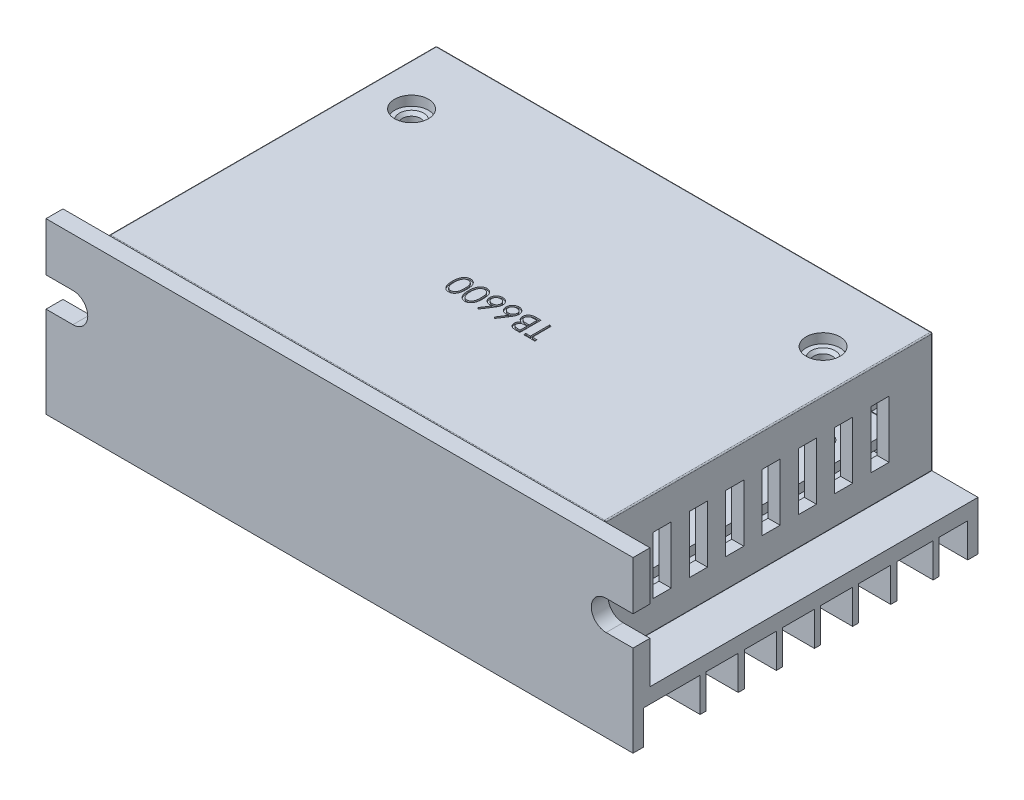
SolidWorks part; units mm, degrees
ref_plane "Front Plane" through (0, 0, 0) normal (0, 0, 1) x (1, 0, 0)
ref_plane "Top Plane" through (0, 0, 0) normal (0, 1, 0) x (1, 0, 0)
ref_plane "Right Plane" through (0, 0, 0) normal (1, 0, 0) x (0, 0, -1)
sketch "Sketch1" plane through (0, 0, 0) normal (1, 0, 0) x (0, 0, -1)
  line L1 (-28.5, 14) -> (28.5, 14)
  line L2 (-28.5, 14) -> (-28.5, -14)
  line L3 (-28.5, -14) -> (28.5, -14)
  line L4 (28.5, 14) -> (28.5, -14)
  line L5 (-28.5, 14) -> (28.5, -14) construction
  line L6 (-28.5, -14) -> (28.5, 14) construction
  point P0 (0, 0)
  dimension "D1" = 28
  dimension "D2" = 57
extrude "Base and Heat Sink" add sketch "Sketch1" along normal mid plane 97
sketch "Sketch2" plane through (0, 0, 0) normal (1, 0, 0) x (0, 0, -1)
  line L0 (28.5, 14) -> (-28.5, 14) construction
  line L1 (-25.7, 14) -> (28.5, 14)
  line L2 (-25.7, 14) -> (-25.7, -5.88)
  line L3 (-25.7, -5.88) -> (28.5, -5.88)
  line L4 (28.5, 14) -> (28.5, -5.88)
  line L5 (28.5, -14) -> (28.5, 14) construction
  line L6 (-28.5, 14) -> (-28.5, -14) construction
  line L7 (-28.5, -14) -> (28.5, -14) construction
  dimension "D1" = 2.8
  dimension "D2" = 8.12
extrude "Cut-Extrude1" cut sketch "Sketch2" against normal through all both and the other way through all
sketch "Sketch3" plane through (0, 0, 0) normal (1, 0, 0) x (0, 0, -1)
  line L0 (-28.5, -14) -> (28.5, -14) construction
  line L1 (-26.8, -14) -> (-17.42, -14)
  line L2 (-26.8, -14) -> (-26.8, -8.38)
  line L3 (-26.8, -8.38) -> (-17.42, -8.38)
  line L4 (-17.42, -14) -> (-17.42, -8.38)
  line L5 (-28.5, 14) -> (-28.5, -14) construction
  line L6 (-25.7, -5.88) -> (28.5, -5.88) construction
  line L7 (-10.12, -14) -> (-10.12, -8.38)
  line L8 (-16.42, -14) -> (-11.12, -14)
  line L9 (-16.42, -14) -> (-16.42, -8.38)
  line L10 (-16.42, -8.38) -> (-11.12, -8.38)
  line L11 (-11.12, -14) -> (-11.12, -8.38)
  line L12 (-10.12, -14) -> (-4.82, -14)
  line L13 (-4.82, -14) -> (-4.82, -8.38)
  line L14 (-3.82, -14) -> (-3.82, -8.38)
  line L15 (-3.82, -14) -> (1.48, -14)
  line L16 (1.48, -14) -> (1.48, -8.38)
  line L17 (2.48, -14) -> (2.48, -8.38)
  line L18 (2.48, -14) -> (7.78, -14)
  line L19 (7.78, -14) -> (7.78, -8.38)
  line L20 (8.78, -14) -> (8.78, -8.38)
  line L21 (8.78, -14) -> (14.08, -14)
  line L22 (14.08, -14) -> (14.08, -8.38)
  line L23 (28.5, -14) -> (28.5, -5.88) construction
  line L24 (15.08, -14) -> (21.08, -14)
  line L25 (15.08, -14) -> (15.08, -8.38)
  line L26 (15.08, -8.38) -> (21.08, -8.38)
  line L27 (21.08, -14) -> (21.08, -8.38)
  line L28 (22.08, -14) -> (26.8, -14)
  line L29 (22.08, -14) -> (22.08, -8.38)
  line L30 (22.08, -8.38) -> (26.8, -8.38)
  line L31 (26.8, -14) -> (26.8, -8.38)
  line L32 (-10.12, -8.38) -> (-4.82, -8.38)
  line L33 (-3.82, -8.38) -> (1.48, -8.38)
  line L34 (2.48, -8.38) -> (7.78, -8.38)
  line L35 (8.78, -8.38) -> (14.08, -8.38)
  dimension "D1" = 1.7
  dimension "D2" = 9.38
  dimension "D3" = 2.5
  dimension "D4" = 1
  dimension "D5" = 5.3
  dimension "D7" = 1
  dimension "D8" = 1
  dimension "D9" = 1
  dimension "D10" = 6
  dimension "D11" = 1
  dimension "D12" = 1.7
  dimension "D6" = 5
extrude "Cut-Extrude2" cut sketch "Sketch3" against normal through all both and the other way through all
sketch "Sketch4" plane through (0, -5.88, 0) normal (0, 1, 0) x (1, 0, 0)
  line L2 (-34, -20.8) -> (34, -20.8) construction
  line L3 (-34, -20.8) -> (-34, 17.4) construction
  line L4 (-34, 17.4) -> (34, 17.4) construction
  line L5 (34, -20.8) -> (34, 17.4) construction
  line L6 (-34, -20.8) -> (34, 17.4) construction
  line L7 (-34, 17.4) -> (34, -20.8) construction
  line L8 (-48.5, 28.5) -> (48.5, 28.5) construction
  circle A0 centre (-34, 17.4) radius 1.5
  circle A1 centre (34, 17.4) radius 1.5
  circle A2 centre (34, -20.8) radius 1.5
  circle A3 centre (-34, -20.8) radius 1.5
  point P0 (0, -1.7)
  dimension "D4" = 3
  dimension "D1" = 68
  dimension "D2" = 11.1
  dimension "D3" = 38.2
extrude "Cut-Extrude3" cut sketch "Sketch4" against normal blind 3
sketch "Sketch5" plane through (0, 0, 28.5) normal (0, 0, 1) x (1, 0, 0)
  line L0 (-48.5, 3.5) -> (52.8108, 3.5) construction
  line L1 (-48.5, 14) -> (-48.5, -14) construction
  line L2 (48.5, 14) -> (-48.5, 14) construction
  line L3 (48.5, 14) -> (48.5, -14) construction
  line L4 (41.6, 6.1377) -> (41.6, 0) construction
  line L5 (44.05, 1.05) -> (48.5, 1.05)
  line L6 (44.05, 5.95) -> (48.5, 5.95)
  line L7 (-41.6, 1.05) -> (-41.6, 6.49) construction
  line L8 (-44.05, 5.95) -> (-48.5, 5.95)
  line L9 (-44.05, 1.05) -> (-48.5, 1.05)
  line L10 (-48.5, 1.05) -> (-48.5, 5.95)
  line L11 (48.5, 1.05) -> (48.5, 5.95)
  arc A0 (44.05, 5.95) -> (44.05, 1.05) centre (44.05, 3.5) ccw
  arc A1 (-44.05, 1.05) -> (-44.05, 5.95) centre (-44.05, 3.5) ccw
  dimension "D2" = 4.9
  dimension "D4" = 6.9
  dimension "D1" = 10.5
  dimension "D3" = 4.45
extrude "Cut-Extrude4" cut sketch "Sketch5" against normal blind 3
sketch "Sketch6" plane through (0, 0, 0) normal (1, 0, 0) x (0, 0, -1)
  line L0 (-25.7, 14) -> (-25.7, 5.95) construction
  line L1 (-25.7, 14) -> (28.5, 14)
  line L2 (-25.7, 14) -> (-25.7, -5.88)
  line L3 (-25.7, -5.88) -> (28.5, -5.88)
  line L4 (28.5, 14) -> (28.5, -5.88)
  line L5 (-25.7, 14) -> (-28.5, 14) construction
extrude "Plastic Casing" add sketch "Sketch6" along normal mid plane 82 separate body
shell "Shell1" thickness 2
fillet "Fillet1" radius 0.2 11 edges at (-41, -5.88, -1.4) (-41, 4.06, 25.7) (0, 14, 25.7) (-41, 14, -1.4) (0, -5.88, -28.5) (0, 14, -28.5) (-41, 4.06, -28.5) (41, 14, -1.4) (41, 4.06, -28.5) (41, -5.88, -1.4) (41, 4.06, 25.7)
sketch "Sketch9" plane through (0, 14, 0) normal (0, 1, 0) x (1, 0, 0)
  circle A0 centre (-34, 17.4) radius 1.5 construction
  circle A1 centre (34, 17.4) radius 1.5 construction
  circle A2 centre (-34, 17.4) radius 1.5
  circle A3 centre (34, 17.4) radius 1.5
sketch "Sketch10" plane through (0, 12, 0) normal (0, -1, 0) x (1, 0, 0)
  circle A0 centre (34, -17.4) radius 3.975
  circle A1 centre (-34, -17.4) radius 3.975
  dimension "D1" = 7.95
extrude "Boss-Extrude3" add sketch "Sketch10" along normal blind 1.2
sketch "Sketch11" plane through (0, 10.8, 0) normal (0, -1, 0) x (1, 0, 0)
  circle A0 centre (-34, -17.4) radius 1.5 construction
  circle A1 centre (34, -17.4) radius 1.5 construction
  circle A2 centre (-34, -17.4) radius 1.5
  circle A3 centre (34, -17.4) radius 1.5
extrude "Cut-Extrude5" cut sketch "Sketch11" against normal blind 11.2
sketch "Sketch12" plane through (0, 14, 0) normal (0, 1, 0) x (1, 0, 0)
  circle A0 centre (-34, 17.4) radius 2.8
  circle A1 centre (34, 17.4) radius 2.8
  dimension "D1" = 5.6
extrude "Cut-Extrude6" cut sketch "Sketch12" against normal blind 1.6
chamfer "Chamfer1" distance 0.5 angle 45 2 edges at (34, 12.4, -15.9) (-34, 12.4, -15.9)
sketch "Sketch13" plane through (0, 0, -28.5) normal (0, 0, -1) x (-1, 0, 0)
  line L0 (41, 13.8) -> (41, -5.68) construction
  line L1 (-33.9, -0.38) -> (32.5, -0.38)
  line L2 (-33.9, -0.38) -> (-33.9, 10.25)
  line L3 (-33.9, 10.25) -> (32.5, 10.25)
  line L4 (32.5, -0.38) -> (32.5, 10.25)
  line L5 (-41, -5.68) -> (-41, 13.8) construction
  line L6 (-40.8, 14) -> (40.8, 14) construction
  line L7 (40.8, -5.88) -> (-40.8, -5.88) construction
  dimension "D1" = 8.5
  dimension "D2" = 7.1
  dimension "D3" = 3.75
  dimension "D4" = 5.5
extrude "Cut-Extrude7" cut sketch "Sketch13" against normal up to surface (2 mm away) up to face at (0, 3.06, -26.5)
sketch "Sketch14" plane through (0, 0, 0) normal (1, 0, 0) x (0, 0, -1)
  line L0 (28.5, -5.68) -> (28.5, 13.8) construction
  line L1 (21.3, 8.45) -> (18.3, 8.45)
  line L2 (21.3, 8.45) -> (21.3, -1.0244)
  line L3 (21.3, -1.0244) -> (18.3, -1.0244)
  line L4 (18.3, 8.45) -> (18.3, -1.0244)
  line L5 (28.3, 14) -> (-25.5, 14) construction
  line L7 (15.3, 8.45) -> (12.3, 8.45)
  line L8 (15.3, 8.45) -> (15.3, -1.0244)
  line L9 (15.3, -1.0244) -> (12.3, -1.0244)
  line L10 (12.3, 8.45) -> (12.3, -1.0244)
  line L11 (9.3, 8.45) -> (6.3, 8.45)
  line L12 (9.3, 8.45) -> (9.3, -1.0244)
  line L13 (9.3, -1.0244) -> (6.3, -1.0244)
  line L14 (6.3, 8.45) -> (6.3, -1.0244)
  line L15 (3.3, 8.45) -> (0.3, 8.45)
  line L16 (3.3, 8.45) -> (3.3, -1.0244)
  line L17 (3.3, -1.0244) -> (0.3, -1.0244)
  line L18 (0.3, 8.45) -> (0.3, -1.0244)
  line L19 (-2.7, 8.45) -> (-5.7, 8.45)
  line L20 (-2.7, 8.45) -> (-2.7, -1.0244)
  line L21 (-2.7, -1.0244) -> (-5.7, -1.0244)
  line L22 (-5.7, 8.45) -> (-5.7, -1.0244)
  line L23 (-8.7, 8.45) -> (-11.7, 8.45)
  line L24 (-8.7, 8.45) -> (-8.7, -1.0244)
  line L25 (-8.7, -1.0244) -> (-11.7, -1.0244)
  line L26 (-11.7, 8.45) -> (-11.7, -1.0244)
  line L27 (-14.7, 8.45) -> (-17.7, 8.45)
  line L28 (-14.7, 8.45) -> (-14.7, -1.0244)
  line L29 (-14.7, -1.0244) -> (-17.7, -1.0244)
  line L30 (-17.7, 8.45) -> (-17.7, -1.0244)
  dimension "D1" = 7.2
  dimension "D2" = 3
  dimension "D3" = 5.55
  dimension "D4" = 7
extrude "Cut-Extrude9" cut sketch "Sketch14" along normal up to surface (41 mm away) up to face at (41, 4.06, -1.4)
sketch "Sketch15" plane through (-41, 0, 0) normal (-1, 0, 0) x (0, 0, 1)
  line L0 (14.7, 8.45) -> (14.7, -1.0244) construction
  line L1 (17.7, 8.45) -> (14.7, 8.45) construction
  line L2 (17.7, -1.0244) -> (17.7, 8.45) construction
  line L3 (14.7, -1.0244) -> (17.7, -1.0244) construction
  line L4 (8.7, -1.0244) -> (11.7, -1.0244) construction
  line L5 (8.7, 8.45) -> (8.7, -1.0244) construction
  line L6 (11.7, 8.45) -> (8.7, 8.45) construction
  line L7 (11.7, -1.0244) -> (11.7, 8.45) construction
  line L8 (-21.3, -1.0244) -> (-18.3, -1.0244) construction
  line L9 (-21.3, 8.45) -> (-21.3, -1.0244) construction
  line L10 (-18.3, 8.45) -> (-21.3, 8.45) construction
  line L11 (-18.3, -1.0244) -> (-18.3, 8.45) construction
  line L12 (14.7, 8.45) -> (14.7, -1.0244)
  line L13 (17.7, 8.45) -> (14.7, 8.45)
  line L14 (17.7, -1.0244) -> (17.7, 8.45)
  line L15 (14.7, -1.0244) -> (17.7, -1.0244)
  line L16 (8.7, -1.0244) -> (11.7, -1.0244)
  line L17 (8.7, 8.45) -> (8.7, -1.0244)
  line L18 (11.7, 8.45) -> (8.7, 8.45)
  line L19 (11.7, -1.0244) -> (11.7, 8.45)
  line L20 (-21.3, -1.0244) -> (-18.3, -1.0244)
  line L21 (-21.3, 8.45) -> (-21.3, -1.0244)
  line L22 (-18.3, 8.45) -> (-21.3, 8.45)
  line L23 (-18.3, -1.0244) -> (-18.3, 8.45)
extrude "Cut-Extrude10" cut sketch "Sketch15" against normal up to surface (2 mm away) up to face at (-39, 3.06, -0.4)
sketch "Sketch16" plane through (-41, 0, 0) normal (-1, 0, 0) x (0, 0, 1)
  line L0 (25.7, -5.88) -> (-28.3, -5.88) construction
  line L1 (-15.1674, 10.82) -> (3.6826, 10.82)
  line L2 (-15.1674, 10.82) -> (-15.1674, 0.62)
  line L3 (-15.1674, 0.62) -> (3.6826, 0.62)
  line L4 (3.6826, 10.82) -> (3.6826, 0.62)
  dimension "D1" = 18.85
  dimension "D2" = 10.2
  dimension "D3" = 6.5
extrude "Cut-Extrude11" cut sketch "Sketch16" against normal up to surface (2 mm away) up to face at (-39, 3.7128, 10.2)
ref_plane "Plane1" through (0, -0.88, 0) normal (0, 1, 0) x (1, 0, 0)
sketch "Sketch17" plane through (0, -0.88, 0) normal (0, 1, 0) x (1, 0, 0)
  line L0 (-48.5, -25.7) -> (48.5, -25.7) construction
  line L1 (38.275, -24.7) -> (-38.275, -24.7)
  line L2 (38.275, -24.7) -> (38.275, 25.4)
  line L3 (38.275, 25.4) -> (-38.275, 25.4)
  line L4 (-38.275, -24.7) -> (-38.275, 25.4)
  circle A0 centre (-34, -20.8) radius 1.5 construction
  circle A1 centre (-34, 17.4) radius 1.5 construction
  circle A2 centre (34, 17.4) radius 1.5 construction
  circle A3 centre (34, -20.8) radius 1.5 construction
  circle A4 centre (-34, -20.8) radius 1.5
  circle A5 centre (-34, 17.4) radius 1.5
  circle A6 centre (34, 17.4) radius 1.5
  circle A7 centre (34, -20.8) radius 1.5
  point P18 (0, -24.7)
  dimension "D1" = 50.1
  dimension "D2" = 1
  dimension "D3" = 76.55
extrude "Boss-Extrude4" add sketch "Sketch17" along normal blind 1.5 separate body
ref_plane "Plane2" through (0, 0, -33.5) normal (0, 0, -1) x (-1, 0, 0)
sketch "Sketch18" plane through (0, 0, -33.5) normal (0, 0, -1) x (-1, 0, 0)
  line L0 (-38.275, 0.62) -> (38.275, 0.62) construction
  line L1 (-33.9, 0.62) -> (27.4, 0.62)
  line L2 (-33.9, 0.62) -> (-33.9, 8.62)
  line L3 (-33.9, 8.62) -> (27.4, 8.62)
  line L4 (27.4, 0.62) -> (27.4, 8.62)
  line L5 (-33.9, 10.25) -> (-33.9, -0.38) construction
  dimension "D1" = 8
  dimension "D2" = 61.3
extrude "Connector" add sketch "Sketch18" against normal blind 12 separate body
sketch "Sketch19" plane through (0, 0, -33.5) normal (0, 0, -1) x (-1, 0, 0)
  line L0 (-3.3029, 9.6458) -> (-3.3029, -7.8401) construction
  line L1 (-33.9, 7.1295) -> (-33.9, 1.6983) construction
  line L2 (-33.9, 8.62) -> (-33.9, 0.62) construction
  line L3 (-28.7917, 7.1867) -> (-28.7917, 1.7555) construction
  line L4 (-23.6833, 7.2439) -> (-23.6833, 1.8127) construction
  line L5 (-18.575, 7.3012) -> (-18.575, 1.8699) construction
  line L6 (-13.4667, 7.3584) -> (-13.4667, 1.9272) construction
  line L7 (-8.3583, 7.4156) -> (-8.3583, 1.9844) construction
  line L8 (-3.25, 7.4728) -> (-3.25, 2.0416) construction
  line L9 (1.8583, 7.53) -> (1.8583, 2.0988) construction
  line L10 (6.9667, 7.5873) -> (6.9667, 2.1561) construction
  line L11 (12.075, 7.6445) -> (12.075, 2.2133) construction
  line L12 (17.1833, 7.7017) -> (17.1833, 2.2705) construction
  line L13 (22.2917, 7.7589) -> (22.2917, 2.3277) construction
  line L14 (27.4, 7.8162) -> (27.4, 2.385) construction
  line L15 (-33.9, 7.1295) -> (-28.7917, 7.1867) construction
  dimension "D2" = 5.1087
  dimension "D1" = 13
sketch "Sketch20" plane through (0, 0, -33.5) normal (0, 0, -1) x (-1, 0, 0)
  line L0 (-33.9, 8.62) -> (-33.9, 0.62) construction
  line L1 (-33.9, 7.02) -> (27.4, 7.02)
  line L2 (-33.9, 7.02) -> (-33.9, 1.62)
  line L3 (-33.9, 1.62) -> (-33.3515, 1.62)
  line L4 (27.4, 7.02) -> (27.4, 1.62)
  line L5 (27.4, 0.62) -> (27.4, 8.62) construction
  line L6 (27.4, 8.62) -> (-33.9, 8.62) construction
  line L7 (-31.3458, 16.2754) -> (-31.3458, 1.62) construction
  line L8 (-28.7917, 7.1867) -> (-28.7917, 1.7555) construction
  line L9 (-29.3401, 1.62) -> (-28.2394, 1.62)
  line L10 (24.8458, 7.7121) -> (24.8458, 1.62) construction
  line L11 (22.2917, 7.7589) -> (22.2917, 2.3277) construction
  line L12 (-33.3515, 1.62) -> (-28.2402, 1.6208) construction
  line L13 (-24.2297, 1.62) -> (-23.1272, 1.62)
  line L14 (-19.1193, 1.62) -> (-18.0151, 1.62)
  line L15 (-14.0089, 1.62) -> (-12.9029, 1.62)
  line L16 (-8.8985, 1.62) -> (-7.7907, 1.62)
  line L17 (-3.7881, 1.62) -> (-2.6786, 1.62)
  line L18 (1.3223, 1.62) -> (2.4336, 1.62)
  line L19 (6.4327, 1.62) -> (7.5458, 1.62)
  line L20 (11.5432, 1.62) -> (12.6579, 1.62)
  line L21 (16.6536, 1.62) -> (17.7701, 1.62)
  line L22 (21.764, 1.62) -> (22.8823, 1.62)
  line L23 (26.8744, 1.62) -> (27.4, 1.62)
  arc A0 (-33.3515, 1.62) -> (-29.3401, 1.62) centre (-31.3458, 3.7715) ccw
  arc A1 (-28.2394, 1.62) -> (-24.2297, 1.62) centre (-26.2345, 3.7723) ccw
  arc A2 (-23.1272, 1.62) -> (-19.1193, 1.62) centre (-21.1233, 3.7731) ccw
  arc A3 (-18.0151, 1.62) -> (-14.0089, 1.62) centre (-16.012, 3.7739) ccw
  arc A4 (-12.9029, 1.62) -> (-8.8985, 1.62) centre (-10.9007, 3.7748) ccw
  arc A5 (-7.7907, 1.62) -> (-3.7881, 1.62) centre (-5.7894, 3.7756) ccw
  arc A6 (-2.6786, 1.62) -> (1.3223, 1.62) centre (-0.6781, 3.7764) ccw
  arc A7 (2.4336, 1.62) -> (6.4327, 1.62) centre (4.4332, 3.7772) ccw
  arc A8 (7.5458, 1.62) -> (11.5432, 1.62) centre (9.5445, 3.778) ccw
  arc A9 (12.6579, 1.62) -> (16.6536, 1.62) centre (14.6557, 3.7788) ccw
  arc A10 (17.7701, 1.62) -> (21.764, 1.62) centre (19.767, 3.7796) ccw
  arc A11 (22.8823, 1.62) -> (26.8744, 1.62) centre (24.8783, 3.7804) ccw
  dimension "D5" = 2.9414
  dimension "D1" = 5.4
  dimension "D2" = 1.6
  dimension "D4" = 5.1113
  dimension "D3" = 12
extrude "Cut-Extrude12" cut sketch "Sketch20" against normal blind 10.5
sketch "Sketch21" plane through (0, 0, -23) normal (0, 0, -1) x (-1, 0, 0)
  line L0 (-31.3458, 6.0298) -> (-31.3458, 2.1596) construction
  line L1 (-33.9, 7.1295) -> (-33.9, 1.6983) construction
  line L2 (-28.7917, 7.1867) -> (-28.7917, 1.7555) construction
  line L3 (-31.3458, 4.0947) -> (24.8458, 4.0947) construction
  line L4 (24.8458, 6.0298) -> (24.8458, 2.1596) construction
  line L5 (22.2917, 7.7589) -> (22.2917, 2.3277) construction
  line L6 (27.4, 7.8162) -> (27.4, 2.385) construction
  line L7 (-26.4875, 4.3447) -> (-25.9875, 4.3447)
  line L8 (-31.5958, 4.3447) -> (-31.0958, 4.3447)
  line L9 (-31.5958, 4.3447) -> (-31.5958, 3.8447)
  line L10 (-31.5958, 3.8447) -> (-31.0958, 3.8447)
  line L11 (-31.0958, 4.3447) -> (-31.0958, 3.8447)
  line L12 (-31.5958, 4.3447) -> (-31.0958, 3.8447) construction
  line L13 (-31.5958, 3.8447) -> (-31.0958, 4.3447) construction
  line L14 (-26.4875, 4.3447) -> (-26.4875, 3.8447)
  line L15 (-26.4875, 3.8447) -> (-25.9875, 3.8447)
  line L16 (-25.9875, 4.3447) -> (-25.9875, 3.8447)
  line L17 (-26.4875, 4.3447) -> (-25.9875, 3.8447) construction
  line L18 (-26.4875, 3.8447) -> (-25.9875, 4.3447) construction
  line L19 (-21.3792, 4.3447) -> (-20.8792, 4.3447)
  line L20 (-21.3792, 4.3447) -> (-21.3792, 3.8447)
  line L21 (-21.3792, 3.8447) -> (-20.8792, 3.8447)
  line L22 (-20.8792, 4.3447) -> (-20.8792, 3.8447)
  line L23 (-21.3792, 4.3447) -> (-20.8792, 3.8447) construction
  line L24 (-21.3792, 3.8447) -> (-20.8792, 4.3447) construction
  line L25 (-16.2708, 4.3447) -> (-15.7708, 4.3447)
  line L26 (-16.2708, 4.3447) -> (-16.2708, 3.8447)
  line L27 (-16.2708, 3.8447) -> (-15.7708, 3.8447)
  line L28 (-15.7708, 4.3447) -> (-15.7708, 3.8447)
  line L29 (-16.2708, 4.3447) -> (-15.7708, 3.8447) construction
  line L30 (-16.2708, 3.8447) -> (-15.7708, 4.3447) construction
  line L31 (-11.1625, 4.3447) -> (-10.6625, 4.3447)
  line L32 (-11.1625, 4.3447) -> (-11.1625, 3.8447)
  line L33 (-11.1625, 3.8447) -> (-10.6625, 3.8447)
  line L34 (-10.6625, 4.3447) -> (-10.6625, 3.8447)
  line L35 (-11.1625, 4.3447) -> (-10.6625, 3.8447) construction
  line L36 (-11.1625, 3.8447) -> (-10.6625, 4.3447) construction
  line L37 (-6.0542, 4.3447) -> (-5.5542, 4.3447)
  line L38 (-6.0542, 4.3447) -> (-6.0542, 3.8447)
  line L39 (-6.0542, 3.8447) -> (-5.5542, 3.8447)
  line L40 (-5.5542, 4.3447) -> (-5.5542, 3.8447)
  line L41 (-6.0542, 4.3447) -> (-5.5542, 3.8447) construction
  line L42 (-6.0542, 3.8447) -> (-5.5542, 4.3447) construction
  line L43 (-0.9458, 4.3447) -> (-0.4458, 4.3447)
  line L44 (-0.9458, 4.3447) -> (-0.9458, 3.8447)
  line L45 (-0.9458, 3.8447) -> (-0.4458, 3.8447)
  line L46 (-0.4458, 4.3447) -> (-0.4458, 3.8447)
  line L47 (-0.9458, 4.3447) -> (-0.4458, 3.8447) construction
  line L48 (-0.9458, 3.8447) -> (-0.4458, 4.3447) construction
  line L49 (4.1625, 4.3447) -> (4.6625, 4.3447)
  line L50 (4.1625, 4.3447) -> (4.1625, 3.8447)
  line L51 (4.1625, 3.8447) -> (4.6625, 3.8447)
  line L52 (4.6625, 4.3447) -> (4.6625, 3.8447)
  line L53 (4.1625, 4.3447) -> (4.6625, 3.8447) construction
  line L54 (4.1625, 3.8447) -> (4.6625, 4.3447) construction
  line L55 (9.2708, 4.3447) -> (9.7708, 4.3447)
  line L56 (9.2708, 4.3447) -> (9.2708, 3.8447)
  line L57 (9.2708, 3.8447) -> (9.7708, 3.8447)
  line L58 (9.7708, 4.3447) -> (9.7708, 3.8447)
  line L59 (9.2708, 4.3447) -> (9.7708, 3.8447) construction
  line L60 (9.2708, 3.8447) -> (9.7708, 4.3447) construction
  line L61 (14.3792, 4.3447) -> (14.8792, 4.3447)
  line L62 (14.3792, 4.3447) -> (14.3792, 3.8447)
  line L63 (14.3792, 3.8447) -> (14.8792, 3.8447)
  line L64 (14.8792, 4.3447) -> (14.8792, 3.8447)
  line L65 (14.3792, 4.3447) -> (14.8792, 3.8447) construction
  line L66 (14.3792, 3.8447) -> (14.8792, 4.3447) construction
  line L67 (19.4875, 4.3447) -> (19.9875, 4.3447)
  line L68 (19.4875, 4.3447) -> (19.4875, 3.8447)
  line L69 (19.4875, 3.8447) -> (19.9875, 3.8447)
  line L70 (19.9875, 4.3447) -> (19.9875, 3.8447)
  line L71 (19.4875, 4.3447) -> (19.9875, 3.8447) construction
  line L72 (19.4875, 3.8447) -> (19.9875, 4.3447) construction
  line L73 (24.5958, 4.3447) -> (25.0958, 4.3447)
  line L74 (24.5958, 4.3447) -> (24.5958, 3.8447)
  line L75 (24.5958, 3.8447) -> (25.0958, 3.8447)
  line L76 (25.0958, 4.3447) -> (25.0958, 3.8447)
  line L77 (24.5958, 4.3447) -> (25.0958, 3.8447) construction
  line L78 (24.5958, 3.8447) -> (25.0958, 4.3447) construction
  line L79 (-31.5958, 4.3447) -> (-26.4875, 4.3447) construction
  dimension "D1" = 0.5
  dimension "D2" = 0.5
  dimension "D4" = 5.1083
  dimension "D3" = 12
extrude "Boss-Extrude6" add sketch "Sketch21" along normal blind 10.5
chamfer "Chamfer2" distance 0.6 angle 15 48 edges at (-24.8458, 3.8447, -33.5) (-24.5958, 4.0947, -33.5) (-24.8458, 4.3447, -33.5) (-25.0958, 4.0947, -33.5) (-19.7375, 3.8447, -33.5) (-19.4875, 4.0947, -33.5) (-19.7375, 4.3447, -33.5) (-19.9875, 4.0947, -33.5) (-14.6292, 3.8447, -33.5) (-14.3792, 4.0947, -33.5) (-14.6292, 4.3447, -33.5) (-14.8792, 4.0947, -33.5) (-9.5208, 3.8447, -33.5) (-9.2708, 4.0947, -33.5) (-9.5208, 4.3447, -33.5) (-9.7708, 4.0947, -33.5) (-4.4125, 3.8447, -33.5) (-4.1625, 4.0947, -33.5) (-4.4125, 4.3447, -33.5) (-4.6625, 4.0947, -33.5) (0.6958, 3.8447, -33.5) (0.9458, 4.0947, -33.5) (0.6958, 4.3447, -33.5) (0.4458, 4.0947, -33.5) (5.8042, 3.8447, -33.5) (6.0542, 4.0947, -33.5) (5.8042, 4.3447, -33.5) (5.5542, 4.0947, -33.5) (10.9125, 3.8447, -33.5) (11.1625, 4.0947, -33.5) (10.9125, 4.3447, -33.5) (10.6625, 4.0947, -33.5) (16.0208, 3.8447, -33.5) (16.2708, 4.0947, -33.5) (16.0208, 4.3447, -33.5) (15.7708, 4.0947, -33.5) (21.1292, 3.8447, -33.5) (21.3792, 4.0947, -33.5) (21.1292, 4.3447, -33.5) (20.8792, 4.0947, -33.5) (26.2375, 3.8447, -33.5) (26.4875, 4.0947, -33.5) (26.2375, 4.3447, -33.5) (25.9875, 4.0947, -33.5) (31.3458, 3.8447, -33.5) (31.5958, 4.0947, -33.5) (31.3458, 4.3447, -33.5) (31.0958, 4.0947, -33.5)
ref_plane "Lights" through (0, 0, -29.5) normal (0, 0, -1) x (-1, 0, 0)
sketch "Sketch22" plane through (0, 0, -29.5) normal (0, 0, -1) x (-1, 0, 0)
  line L0 (27.4, 0.62) -> (27.4, 8.62) construction
  line L1 (27.4, 0.62) -> (32.5, 0.62)
  line L2 (27.4, 0.62) -> (27.4, 10.25)
  line L3 (27.4, 10.25) -> (32.5, 10.25)
  line L4 (32.5, 0.62) -> (32.5, 10.25)
  line L5 (-38.275, 0.62) -> (38.275, 0.62) construction
extrude "Boss-Extrude7" add sketch "Sketch22" against normal blind 9 separate body
sketch "Sketch23" plane through (0, 0, -29.5) normal (0, 0, -1) x (-1, 0, 0)
  line L0 (29.95, 10.25) -> (29.95, 0.62) construction
  line L1 (32.5, 10.25) -> (27.4, 10.25) construction
  line L2 (27.4, 0.62) -> (32.5, 0.62) construction
  circle A0 centre (29.95, 7.04) radius 1
  dimension "D2" = 2
  dimension "D4" = 3.21
extrude "Boss-Extrude8" add sketch "Sketch23" along normal blind 4 separate body
sketch "Sketch24" plane through (0, 0, -33.5) normal (0, 0, -1) x (-1, 0, 0)
  line L0 (29.95, 8.2458) -> (29.95, 5.8056) construction
ref_plane "Plane4" through (-29.95, 0, 0) normal (-1, 0, 0) x (0, 0, 1)
sketch "Sketch26" plane through (-29.95, 0, 0) normal (-1, 0, 0) x (0, 0, 1)
  line L0 (-33.8971, 7.04) -> (-31.2542, 7.04) construction
  line L3 (-33.5, 6.04) -> (-32.3126, 6.04) construction
  line L6 (-33.5, 8.04) -> (-33.5, 6.04) construction
  line L7 (-33.5, 8.04) -> (-32.6838, 8.04) construction
  line L8 (-29.5, 10.714) -> (-29.5, -10.714) construction
  line L9 (-33, 7.04) -> (-33.7369, 7.04)
  line L10 (-33.7369, 7.04) -> (-33.7369, 6.04)
  line L11 (-33.7369, 6.04) -> (-32, 6.04)
  arc A0 (-33, 7.04) -> (-32, 6.04) centre (-32, 7.04) ccw
  dimension "D2" = 2
  dimension "D1" = 1
  dimension "D3" = 2.5
revolve "Cut-Revolve2" cut sketch "Sketch26" angle 360 about L0
sketch "Sketch27" plane through (0, 0, -29.5) normal (0, 0, -1) x (-1, 0, 0)
  line L0 (29.95, 10.25) -> (29.95, 0.6198) construction
  line L1 (32.5, 10.25) -> (27.4, 10.25) construction
  line L2 (29.95, -5.2965) -> (29.95, 5.2965) construction
  line L3 (27.4, 0.62) -> (32.5, 0.62) construction
  circle A0 centre (29.95, 3.83) radius 1
  dimension "D1" = 2
  dimension "D2" = 3.21
extrude "Boss-Extrude9" add sketch "Sketch27" along normal blind 4 separate body
sketch "Sketch28" plane through (-29.95, 0, 0) normal (-1, 0, 0) x (0, 0, 1)
  line L0 (-33.7212, 3.83) -> (-29.3271, 3.83) construction
  line L1 (-29.5, 4.83) -> (-33.5, 4.83) construction
  line L2 (-33.5, 2.83) -> (-29.5, 2.83) construction
  line L3 (-32, 8.04) -> (-32, 6.04) construction
  line L4 (-32, 7.04) -> (-32, 2.3515) construction
  line L5 (-32, 2.83) -> (-33.7212, 2.83)
  line L6 (-33.7212, 2.83) -> (-33.7212, 3.83)
  line L7 (-33.7212, 3.83) -> (-33, 3.83)
  arc A0 (-33, 3.83) -> (-32, 2.83) centre (-32, 3.83) ccw
  dimension "D1" = 2
revolve "Cut-Revolve3" cut sketch "Sketch28" angle 360 about L0
sketch "Sketch29" plane through (0, 0.62, 0) normal (0, 1, 0) x (1, 0, 0)
  line L0 (-40.8, 5.7424) -> (-12.823, 5.7424) construction
  line L1 (-40.8, 28.3) -> (-40.8, -25.5) construction
  line L2 (-40, 15.1674) -> (-13.8921, 15.1674) construction
  line L3 (-39, 15.1674) -> (-41, 15.1674) construction
  line L4 (-39, -3.6826) -> (-13.8921, -3.6826) construction
  line L6 (-36.7603, 15.1674) -> (-26.3903, 15.1674)
  line L7 (-36.7603, 15.1674) -> (-36.7603, -3.6826)
  line L8 (-36.7603, -3.6826) -> (-26.3903, -3.6826)
  line L9 (-26.3903, 15.1674) -> (-26.3903, -3.6826)
  dimension "D1" = 9.425
  dimension "D2" = 10.37
extrude "Switch Holder" add sketch "Sketch29" along normal blind 10 separate body
sketch "Sketch30" plane through (-36.7603, 0, 0) normal (-1, 0, 0) x (0, 0, 1)
  line L0 (-15.1674, 10.62) -> (3.6826, 10.62) construction
  line L1 (-13.7174, 10.62) -> (-12.2674, 10.62)
  line L2 (-13.7174, 10.62) -> (-13.7174, 6.5757)
  line L3 (-13.7174, 6.5757) -> (-12.2674, 6.5757)
  line L4 (-12.2674, 10.62) -> (-12.2674, 6.5757)
  line L5 (-13.7174, 10.9969) -> (-13.7174, 4.3932) construction
  line L6 (2.6826, 10.9969) -> (2.6826, 4.3932) construction
  line L7 (3.6826, 10.62) -> (3.6826, 0.62) construction
  line L8 (-15.1674, 10.62) -> (-15.1674, 0.62) construction
  line L9 (-10.8174, 10.62) -> (-9.3674, 10.62)
  line L10 (-10.8174, 10.62) -> (-10.8174, 6.5757)
  line L11 (-10.8174, 6.5757) -> (-9.3674, 6.5757)
  line L12 (-9.3674, 10.62) -> (-9.3674, 6.5757)
  line L13 (-7.9174, 10.62) -> (-6.4674, 10.62)
  line L14 (-7.9174, 10.62) -> (-7.9174, 6.5757)
  line L15 (-7.9174, 6.5757) -> (-6.4674, 6.5757)
  line L16 (-6.4674, 10.62) -> (-6.4674, 6.5757)
  line L17 (-5.0174, 10.62) -> (-3.5674, 10.62)
  line L18 (-5.0174, 10.62) -> (-5.0174, 6.5757)
  line L19 (-5.0174, 6.5757) -> (-3.5674, 6.5757)
  line L20 (-3.5674, 10.62) -> (-3.5674, 6.5757)
  line L21 (-2.1174, 10.62) -> (-0.6674, 10.62)
  line L22 (-2.1174, 10.62) -> (-2.1174, 6.5757)
  line L23 (-2.1174, 6.5757) -> (-0.6674, 6.5757)
  line L24 (-0.6674, 10.62) -> (-0.6674, 6.5757)
  line L25 (0.7826, 10.62) -> (2.2326, 10.62)
  line L26 (0.7826, 10.62) -> (0.7826, 6.5757)
  line L27 (0.7826, 6.5757) -> (2.2326, 6.5757)
  line L28 (2.2326, 10.62) -> (2.2326, 6.5757)
  line L29 (-13.7174, 10.62) -> (-10.8174, 10.62) construction
  dimension "D1" = 1.45
  dimension "D2" = 1
  dimension "D3" = 1.45
  dimension "D4" = 6
  dimension "D5" = 2.9
extrude "Cut-Extrude13" cut sketch "Sketch30" against normal blind 1.5
chamfer "Chamfer3" distance 2 angle 45 1 edges at (-26.3903, 10.62, -5.7424)
sketch "Sketch31" plane through (0, 6.5757, 0) normal (0, 1, 0) x (1, 0, 0)
  line L0 (-35.2603, 12.2674) -> (-36.7603, 12.2674) construction
  line L1 (-35.2603, 13.7174) -> (-36.2603, 13.7174)
  line L2 (-35.2603, 13.7174) -> (-35.2603, 12.2674)
  line L3 (-35.2603, 12.2674) -> (-36.2603, 12.2674)
  line L4 (-36.2603, 13.7174) -> (-36.2603, 12.2674)
  line L5 (-35.2603, 9.3674) -> (-36.7603, 9.3674) construction
  line L6 (-35.2603, 10.8174) -> (-36.2603, 10.8174)
  line L7 (-35.2603, 10.8174) -> (-35.2603, 9.3674)
  line L8 (-35.2603, 9.3674) -> (-36.2603, 9.3674)
  line L9 (-36.2603, 10.8174) -> (-36.2603, 9.3674)
  line L10 (-35.2603, 6.4674) -> (-36.7603, 6.4674) construction
  line L11 (-35.2603, 7.9174) -> (-36.2603, 7.9174)
  line L12 (-35.2603, 7.9174) -> (-35.2603, 6.4674)
  line L13 (-35.2603, 6.4674) -> (-36.2603, 6.4674)
  line L14 (-36.2603, 7.9174) -> (-36.2603, 6.4674)
  line L15 (-35.2603, 3.5674) -> (-36.7603, 3.5674) construction
  line L16 (-35.2603, 5.0174) -> (-36.2603, 5.0174)
  line L17 (-35.2603, 5.0174) -> (-35.2603, 3.5674)
  line L18 (-35.2603, 3.5674) -> (-36.2603, 3.5674)
  line L19 (-36.2603, 5.0174) -> (-36.2603, 3.5674)
  line L20 (-35.2603, 0.6674) -> (-36.7603, 0.6674) construction
  line L21 (-35.2603, 2.1174) -> (-36.2603, 2.1174)
  line L22 (-35.2603, 2.1174) -> (-35.2603, 0.6674)
  line L23 (-35.2603, 0.6674) -> (-36.2603, 0.6674)
  line L24 (-36.2603, 2.1174) -> (-36.2603, 0.6674)
  line L25 (-35.2603, -2.2326) -> (-36.7603, -2.2326) construction
  line L26 (-35.2603, -0.7826) -> (-36.2603, -0.7826)
  line L27 (-35.2603, -0.7826) -> (-35.2603, -2.2326)
  line L28 (-35.2603, -2.2326) -> (-36.2603, -2.2326)
  line L29 (-36.2603, -0.7826) -> (-36.2603, -2.2326)
  dimension "D1" = 1
extrude "Dip Switches" add sketch "Sketch31" along normal up to surface (4.0443 mm away) separate body
sketch "Sketch32" plane through (-36.2603, 0, 0) normal (-1, 0, 0) x (0, 0, 1)
  line L0 (-12.2674, 10.62) -> (-12.2674, 6.5757) construction
  line L1 (-13.7174, 10.62) -> (-12.2674, 10.62)
  line L2 (-13.7174, 10.62) -> (-13.7174, 9.62)
  line L3 (-13.7174, 9.62) -> (-12.2674, 9.62)
  line L4 (-12.2674, 10.62) -> (-12.2674, 9.62)
  line L5 (-9.3674, 10.62) -> (-9.3674, 6.5757) construction
  line L6 (-10.8174, 10.62) -> (-9.3674, 10.62)
  line L7 (-10.8174, 10.62) -> (-10.8174, 9.62)
  line L8 (-10.8174, 9.62) -> (-9.3674, 9.62)
  line L9 (-9.3674, 10.62) -> (-9.3674, 9.62)
  line L10 (-6.4674, 10.62) -> (-6.4674, 6.5757) construction
  line L11 (-7.9174, 10.62) -> (-6.4674, 10.62)
  line L12 (-7.9174, 10.62) -> (-7.9174, 9.62)
  line L13 (-7.9174, 9.62) -> (-6.4674, 9.62)
  line L14 (-6.4674, 10.62) -> (-6.4674, 9.62)
  line L15 (-3.5674, 10.62) -> (-3.5674, 6.5757) construction
  line L16 (-5.0174, 10.62) -> (-3.5674, 10.62)
  line L17 (-5.0174, 10.62) -> (-5.0174, 9.62)
  line L18 (-5.0174, 9.62) -> (-3.5674, 9.62)
  line L19 (-3.5674, 10.62) -> (-3.5674, 9.62)
  line L20 (-0.6674, 10.62) -> (-0.6674, 6.5757) construction
  line L21 (-2.1174, 10.62) -> (-0.6674, 10.62)
  line L22 (-2.1174, 10.62) -> (-2.1174, 9.62)
  line L23 (-2.1174, 9.62) -> (-0.6674, 9.62)
  line L24 (-0.6674, 10.62) -> (-0.6674, 9.62)
  line L25 (2.2326, 10.62) -> (2.2326, 6.5757) construction
  line L26 (0.7826, 10.62) -> (2.2326, 10.62)
  line L27 (0.7826, 10.62) -> (0.7826, 9.5443)
  line L28 (0.7826, 9.5443) -> (2.2326, 9.5443)
  line L29 (2.2326, 10.62) -> (2.2326, 9.5443)
  dimension "D1" = 1
extrude "Boss-Extrude12" add sketch "Sketch32" along normal blind 3.5
sketch "Sketch33" plane through (0, 14, 0) normal (0, 1, 0) x (1, 0, 0)
  line L0 (9.4494, -2.1364) -> (-26.0521, -2.1364) construction
  text T0 "TB6600"
extrude "Cut-Extrude14" cut sketch "Sketch33" against normal blind 0.25
